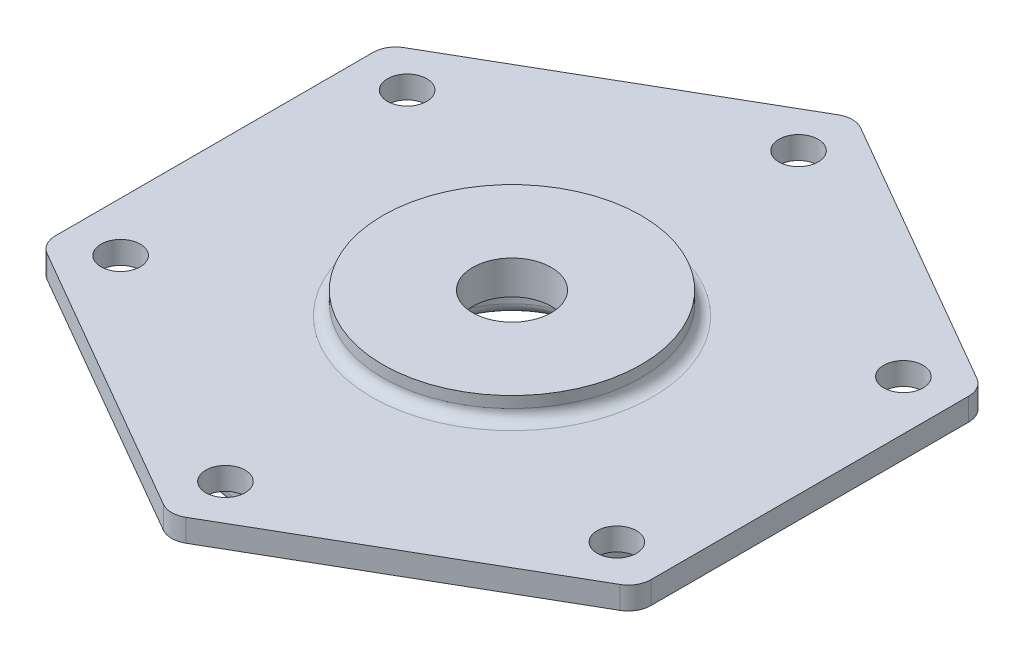
SolidWorks part; units mm, degrees
material "Aluminum Bronze"
ref_plane "Front Plane" through (0, 0, 0) normal (0, 0, 1) x (1, 0, 0)
ref_plane "Top Plane" through (0, 0, 0) normal (0, 1, 0) x (1, 0, 0)
ref_plane "Right Plane" through (0, 0, 0) normal (1, 0, 0) x (0, 0, -1)
sketch "Sketch1" plane through (0, 0, 0) normal (0, 1, 0) x (1, 0, 0)
  line L1 (2, -60.0444) -> (51, -31.7543)
  line L2 (53, -28.2902) -> (53, 28.2902)
  line L3 (51, 31.7543) -> (2, 60.0444)
  line L4 (-2, 60.0444) -> (-51, 31.7543)
  line L5 (-53, 28.2902) -> (-53, -28.2902)
  line L6 (-51, -31.7543) -> (-2, -60.0444)
  circle A0 centre (0, 0) radius 53 construction
  arc A1 (-53, -28.2902) -> (-51, -31.7543) centre (-49, -28.2902) ccw
  arc A2 (-51, 31.7543) -> (-53, 28.2902) centre (-49, 28.2902) ccw
  arc A3 (2, 60.0444) -> (-2, 60.0444) centre (0, 56.5803) ccw
  arc A4 (53, 28.2902) -> (51, 31.7543) centre (49, 28.2902) ccw
  arc A5 (51, -31.7543) -> (53, -28.2902) centre (49, -28.2902) ccw
  arc A6 (2, -60.0444) -> (-2, -60.0444) centre (0, -56.5803) cw
  point P1 (0, 0)
  point P22 (0, -61.1991)
  dimension "D2" = 4
  dimension "D1" = 106
extrude "Boss-Extrude1" add sketch "Sketch1" along normal blind 4
sketch "Sketch2" plane through (0, 4, 0) normal (0, 1, 0) x (1, 0, 0)
  circle A0 centre (0, 0) radius 23
  dimension "D1" = 46
extrude "Boss-Extrude2" add sketch "Sketch2" along normal blind 4
sketch "Sketch3" plane through (0, 0, 0) normal (0, -1, 0) x (1, 0, 0)
  circle A0 centre (0, 0) radius 45
  dimension "D1" = 90
extrude "Boss-Extrude3" add sketch "Sketch3" along normal blind 6
sketch "Sketch4" plane through (0, -6, 0) normal (0, -1, 0) x (1, 0, 0)
  circle A0 centre (0, 0) radius 19
  circle A1 centre (0, 0) radius 40
  dimension "D1" = 80
  dimension "D2" = 38
extrude "Cut-Extrude1" cut sketch "Sketch4" against normal blind 6
sketch "Sketch5" plane through (0, -6, 0) normal (0, -1, 0) x (1, 0, 0)
  circle A0 centre (0, 0) radius 14
  dimension "D1" = 28
extrude "Cut-Extrude2" cut sketch "Sketch5" against normal blind 8
sketch "Sketch6" plane through (0, 2, 0) normal (0, -1, 0) x (1, 0, 0)
  circle A0 centre (0, 0) radius 7
  dimension "D1" = 14
extrude "Cut-Extrude3" cut sketch "Sketch6" against normal through all
fillet "Fillet1" radius 2 5 edges at (0, -6, -45) (0, -6, -40) (0, -6, -19) (0, -6, -14) (0, 4, 23)
sketch "Sketch7" plane through (0, 4, 0) normal (0, 1, 0) x (1, 0, 0)
  circle A0 centre (0, 0) radius 51 construction
  circle A1 centre (0, 51) radius 3.5
  circle A2 centre (44.1673, 25.5) radius 3.5
  circle A3 centre (44.1673, -25.5) radius 3.5
  circle A4 centre (0, -51) radius 3.5
  circle A5 centre (-44.1673, -25.5) radius 3.5
  circle A6 centre (-44.1673, 25.5) radius 3.5
  point P17 (0, 0)
  dimension "D1" = 102
  dimension "D2" = 7
  dimension "D3" = 6
extrude "Cut-Extrude4" cut sketch "Sketch7" against normal through all
